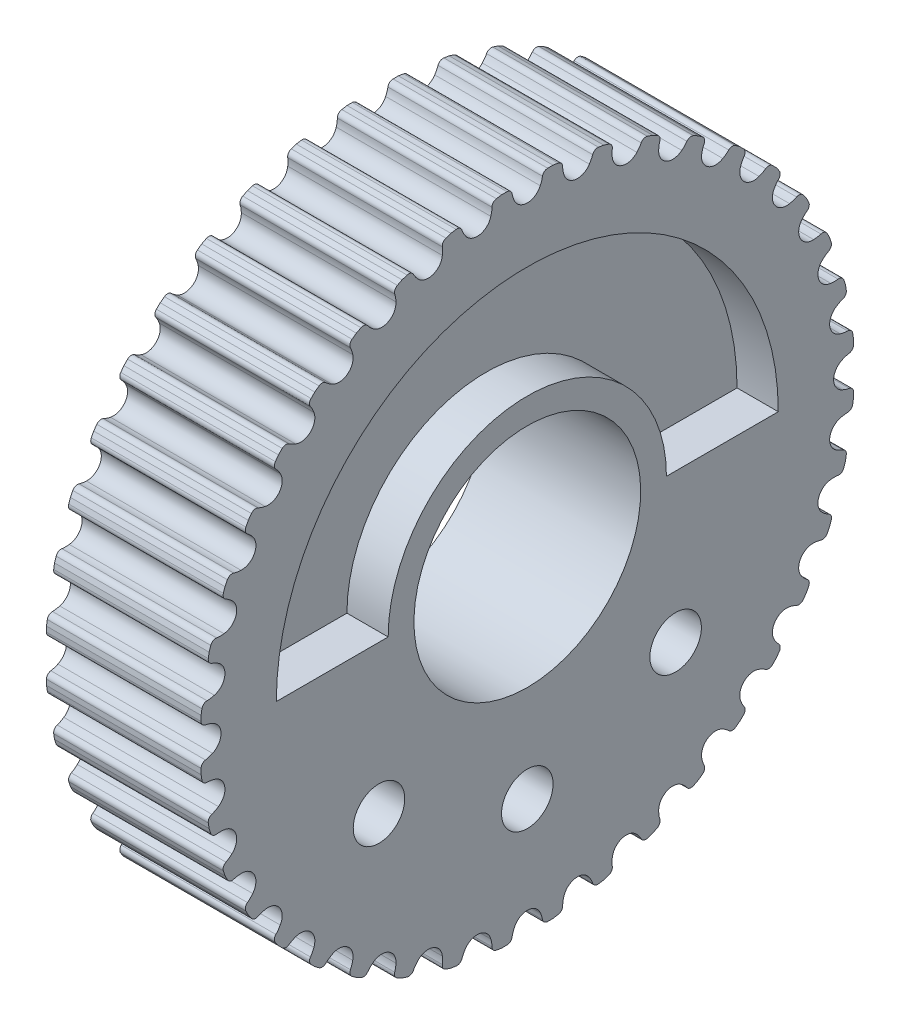
SolidWorks part; units mm, degrees
material "6061 Alloy"
ref_plane "Front Plane" through (0, 0, 0) normal (0, 0, 1) x (1, 0, 0)
ref_plane "Top Plane" through (0, 0, 0) normal (0, 1, 0) x (1, 0, 0)
ref_plane "Right Plane" through (0, 0, 0) normal (1, 0, 0) x (0, 0, -1)
sketch "Sketch1" plane through (0, 0, 0) normal (0, 0, 1) x (1, 0, 0)
  line L0 (85.2676, 0) -> (-189.3195, 0) construction
  line L1 (-44.1011, 0) -> (-44.1011, 13.5)
  line L2 (-44.1011, 13.5) -> (-48.1011, 13.5)
  line L3 (-48.1011, 13.5) -> (-48.1011, 24.35)
  line L4 (-48.1011, 24.35) -> (-44.1011, 24.35)
  line L5 (-44.1011, 24.35) -> (-44.1011, 31.85)
  line L6 (-44.1011, 31.85) -> (-59.1011, 31.85)
  line L7 (-59.1011, 31.85) -> (-59.1011, 24.35)
  line L8 (-59.1011, 24.35) -> (-55.1011, 24.35)
  line L9 (-55.1011, 24.35) -> (-55.1011, 13.5)
  line L10 (-55.1011, 13.5) -> (-59.1011, 13.5)
  line L11 (-59.1011, 13.5) -> (-59.1011, 0)
  line L12 (-59.1011, 0) -> (-44.1011, 0)
  dimension "D1" = 31.85
  dimension "D2" = 15
  dimension "D3" = 7.5
  dimension "D4" = 4
  dimension "D5" = 13.5
revolve "Revolve1" add sketch "Sketch1" angle 360 about L0
sketch "Sketch2" plane through (-59.1011, 0, 0) normal (-1, 0, 0) x (0, 0, 1)
  line L0 (0, -4.2164) -> (0, 48.0832) construction
  line L2 (-1.9771, 31.6489) -> (-2.5, 31.6489)
  line L3 (0, 31.6489) -> (1.03, 31.6489) construction
  line L9 (0, 31.6489) -> (0, 29.7189) construction
  line L10 (0, 29.7189) -> (0, 31.0889) construction
  line L15 (-2.5, 31.6489) -> (-2.5, 33.5189)
  line L16 (-2.5, 33.5189) -> (2.5, 33.5189)
  line L17 (2.5, 31.6489) -> (2.5, 33.5189)
  line L18 (1.9771, 31.6489) -> (2.5, 31.6489)
  arc A10 (1.2559, 30.5416) -> (-1.2559, 30.5416) centre (0, 31.0889) cw
  arc A11 (1.2559, 30.5416) -> (1.4742, 31.2242) centre (-1.03, 31.6489) ccw
  arc A12 (-1.9771, 31.6489) -> (-1.4742, 31.2242) centre (-1.9771, 31.1389) cw
  arc A13 (-1.2559, 30.5416) -> (-1.4742, 31.2242) centre (1.03, 31.6489) cw
  arc A14 (1.9771, 31.6489) -> (1.4742, 31.2242) centre (1.9771, 31.1389) ccw
  point P19 (0, 33.5189)
  dimension "D3" = 2.54
  dimension "D2" = 1.37
  dimension "D1" = 0.51
  dimension "D4" = 52.2996
extrude "Cut-Extrude2" cut sketch "Sketch2" against normal through all
pattern_circular "CirPattern1" count 40 every 9 about axis through (0, 0, 0) along (1, 0, 0) of "Cut-Extrude2"
sketch "Sketch3" plane through (-59.1011, 0, 0) normal (-1, 0, 0) x (0, 0, 1)
  circle A0 centre (0, 0) radius 11
  dimension "D1" = 22
extrude "Cut-Extrude3" cut sketch "Sketch3" against normal through all
sketch "Sketch4" plane through (-59.1011, 0, 0) normal (-1, 0, 0) x (0, 0, 1)
  line L0 (-28.2, 0) -> (-12.5, 0)
  line L1 (12.5, 0) -> (28.2, 0)
  arc A0 (-12.5, 0) -> (12.5, 0) centre (0, 0) ccw
  arc A1 (28.2, 0) -> (-28.2, 0) centre (0, 0) cw
extrude "Boss-Extrude1" add sketch "Sketch4" against normal blind 15
sketch "Sketch5" plane through (-59.1011, 0, 0) normal (-1, 0, 0) x (0, 0, 1)
  line L2 (-28.2, 0) -> (-12.5, 0) construction
  line L3 (12.5, 0) -> (28.2, 0) construction
  arc A1 (28.2, 0) -> (-28.2, 0) centre (0, 0) cw construction
  arc A2 (-12.5, 0) -> (12.5, 0) centre (0, 0) ccw construction
  arc A3 (-20.35, 0) -> (20.35, 0) centre (0, 0) ccw construction
  circle A4 centre (0, -20.35) radius 2.5
  arc A7 (0, -20.35) -> (14.3896, -14.3896) centre (0, 0) ccw construction
  arc A8 (0, -20.35) -> (-14.3896, -14.3896) centre (0, 0) cw construction
  circle A13 centre (-14.3896, -14.3896) radius 2.5
  circle A14 centre (14.3896, -14.3896) radius 2.5
  point P13 (0, 0)
  point P17 (0, 0)
  dimension "D1" = 45
  dimension "D3" = 20.35
  dimension "D2" = 45
  dimension "D4" = 20.35
extrude "Cut-Extrude4" cut sketch "Sketch5" against normal blind 15
